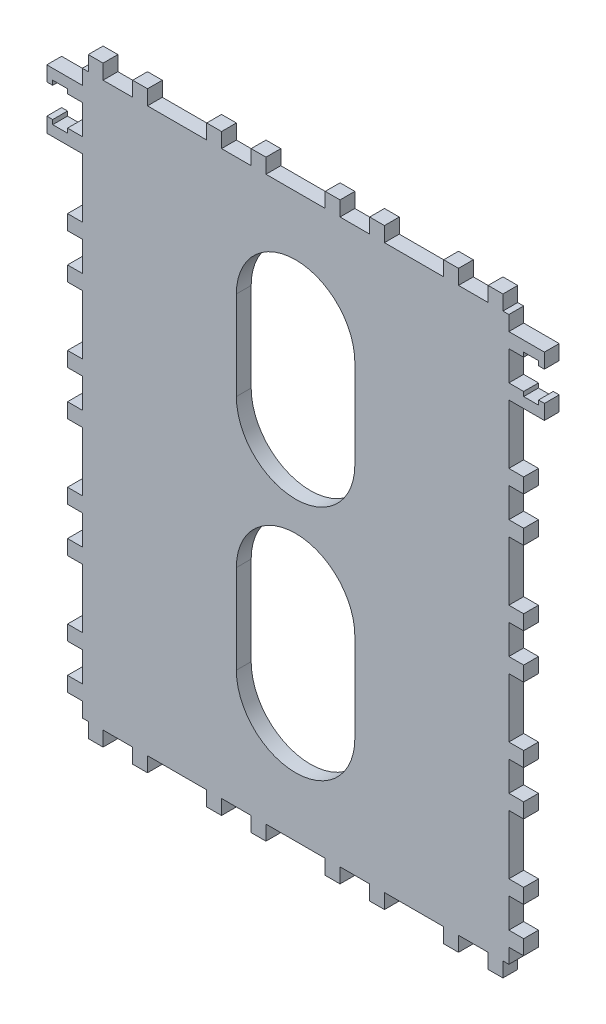
SolidWorks part; units mm, degrees
ref_plane "Plan de face" through (0, 0, 0) normal (0, 0, 1) x (1, 0, 0)
ref_plane "Plan de dessus" through (0, 0, 0) normal (0, 1, 0) x (1, 0, 0)
ref_plane "Plan de droite" through (0, 0, 0) normal (1, 0, 0) x (0, 0, -1)
sketch "Esquisse1" plane through (0, 0, 0) normal (0, 0, 1) x (1, 0, 0)
  line L0 (0, 0) -> (0, 95) construction
  line L1 (-27.1299, 95) -> (22.3044, 95) construction
  line L2 (0, 40) -> (0, 70) construction
  line L3 (-72, 190) -> (-72, 0) construction
  line L4 (-72, 0) -> (-70, 0)
  line L5 (70, 0) -> (72, 0)
  line L6 (-50, 190) -> (-30, 190)
  line L7 (72, 0) -> (72, 190) construction
  line L8 (-20, 40) -> (-20, 70)
  line L9 (50, 190) -> (30, 190)
  line L10 (10, 190) -> (-10, 190)
  line L11 (10, 0) -> (-10, 0)
  line L12 (50, 0) -> (30, 0)
  line L13 (-50, 0) -> (-30, 0)
  line L14 (-72, 5) -> (-72, 0)
  line L15 (-72, 25) -> (-72, 45)
  line L16 (-72, 65) -> (-72, 85)
  line L17 (-72, 105) -> (-72, 125)
  line L18 (-72, 145) -> (-72, 165)
  line L19 (-72, 185) -> (-72, 190)
  line L20 (72, 190) -> (72, 0) construction
  line L21 (72, 185) -> (72, 190)
  line L22 (72, 145) -> (72, 165)
  line L23 (72, 105) -> (72, 125)
  line L24 (72, 65) -> (72, 85)
  line L25 (72, 25) -> (72, 45)
  line L26 (72, 5) -> (72, 0)
  line L27 (70, 190) -> (72, 190)
  line L28 (-72, 190) -> (-70, 190)
  line L29 (20, 40) -> (20, 70)
  line L30 (0, 120) -> (0, 150) construction
  line L31 (-20, 120) -> (-20, 150)
  line L32 (20, 120) -> (20, 150)
  arc A0 (-20, 40) -> (20, 40) centre (0, 40) ccw
  arc A1 (20, 70) -> (-20, 70) centre (0, 70) ccw
  arc A2 (-20, 120) -> (20, 120) centre (0, 120) ccw
  arc A3 (20, 150) -> (-20, 150) centre (0, 150) ccw
  point P15 (0, 55)
  point P46 (0, 135)
  point P59 (0, 20)
  point P60 (0, 0)
  point P61 (0, 0)
  line B0 (-60, 0) -> (-60, 11.1075) construction
  line B1 (-60, 0) -> (-65, 0)
  line B2 (-65, -5) -> (-70, -5)
  line B3 (-70, -5) -> (-70, 0)
  line B4 (-65, -5) -> (-65, 0)
  line B5 (-60, 0) -> (-55, 0)
  line B6 (-55, 0) -> (-55, -5)
  line B7 (-55, -5) -> (-50, -5)
  line B8 (-50, -5) -> (-50, 0)
  line B9 (-20, 0) -> (-20, 11.1075) construction
  line B10 (-20, 0) -> (-25, 0)
  line B11 (-25, -5) -> (-30, -5)
  line B12 (-30, -5) -> (-30, 0)
  line B13 (-25, -5) -> (-25, 0)
  line B14 (-20, 0) -> (-15, 0)
  line B15 (-15, 0) -> (-15, -5)
  line B16 (-15, -5) -> (-10, -5)
  line B17 (-10, -5) -> (-10, 0)
  line B18 (60, 0) -> (60, 11.1075) construction
  line B19 (60, 0) -> (65, 0)
  line B20 (65, -5) -> (70, -5)
  line B21 (70, -5) -> (70, 0)
  line B22 (65, -5) -> (65, 0)
  line B23 (60, 0) -> (55, 0)
  line B24 (55, 0) -> (55, -5)
  line B25 (55, -5) -> (50, -5)
  line B26 (50, -5) -> (50, 0)
  line B27 (-72, 135) -> (-60.8925, 135) construction
  line B28 (-72, 135) -> (-72, 130)
  line B29 (-77, 130) -> (-77, 125)
  line B30 (-77, 125) -> (-72, 125)
  line B31 (-77, 130) -> (-72, 130)
  line B32 (-72, 135) -> (-72, 140)
  line B33 (-72, 140) -> (-77, 140)
  line B34 (-77, 140) -> (-77, 145)
  line B35 (-77, 145) -> (-72, 145)
  line B36 (-72, 95) -> (-60.8925, 95) construction
  line B37 (-72, 95) -> (-72, 90)
  line B38 (-77, 90) -> (-77, 85)
  line B39 (-77, 85) -> (-72, 85)
  line B40 (-77, 90) -> (-72, 90)
  line B41 (-72, 95) -> (-72, 100)
  line B42 (-72, 100) -> (-77, 100)
  line B43 (-77, 100) -> (-77, 105)
  line B44 (-77, 105) -> (-72, 105)
  line B45 (-72, 55) -> (-60.8925, 55) construction
  line B46 (-72, 55) -> (-72, 50)
  line B47 (-77, 50) -> (-77, 45)
  line B48 (-77, 45) -> (-72, 45)
  line B49 (-77, 50) -> (-72, 50)
  line B50 (-72, 55) -> (-72, 60)
  line B51 (-72, 60) -> (-77, 60)
  line B52 (-77, 60) -> (-77, 65)
  line B53 (-77, 65) -> (-72, 65)
  line B54 (-72, 15) -> (-60.8925, 15) construction
  line B55 (-72, 15) -> (-72, 10)
  line B56 (-77, 10) -> (-77, 5)
  line B57 (-77, 5) -> (-72, 5)
  line B58 (-77, 10) -> (-72, 10)
  line B59 (-72, 15) -> (-72, 20)
  line B60 (-72, 20) -> (-77, 20)
  line B61 (-77, 20) -> (-77, 25)
  line B62 (-77, 25) -> (-72, 25)
  line B63 (72, 55) -> (60.8925, 55) construction
  line B64 (72, 55) -> (72, 50)
  line B65 (77, 50) -> (77, 45)
  line B66 (77, 45) -> (72, 45)
  line B67 (77, 50) -> (72, 50)
  line B68 (72, 55) -> (72, 60)
  line B69 (72, 60) -> (77, 60)
  line B70 (77, 60) -> (77, 65)
  line B71 (77, 65) -> (72, 65)
  line B72 (72, 15) -> (60.8925, 15) construction
  line B73 (72, 15) -> (72, 10)
  line B74 (77, 10) -> (77, 5)
  line B75 (77, 5) -> (72, 5)
  line B76 (77, 10) -> (72, 10)
  line B77 (72, 15) -> (72, 20)
  line B78 (72, 20) -> (77, 20)
  line B79 (77, 20) -> (77, 25)
  line B80 (77, 25) -> (72, 25)
  line B81 (72, 95) -> (60.8925, 95) construction
  line B82 (72, 95) -> (72, 90)
  line B83 (77, 90) -> (77, 85)
  line B84 (77, 85) -> (72, 85)
  line B85 (77, 90) -> (72, 90)
  line B86 (72, 95) -> (72, 100)
  line B87 (72, 100) -> (77, 100)
  line B88 (77, 100) -> (77, 105)
  line B89 (77, 105) -> (72, 105)
  line B90 (72, 135) -> (60.8925, 135) construction
  line B91 (72, 135) -> (72, 130)
  line B92 (77, 130) -> (77, 125)
  line B93 (77, 125) -> (72, 125)
  line B94 (77, 130) -> (72, 130)
  line B95 (72, 135) -> (72, 140)
  line B96 (72, 140) -> (77, 140)
  line B97 (77, 140) -> (77, 145)
  line B98 (77, 145) -> (72, 145)
  line B99 (72, 175) -> (60.135, 175) construction
  line B100 (72, 175) -> (72, 170)
  line B101 (77, 170) -> (77, 165) construction
  line B102 (77, 165) -> (72, 165)
  line B103 (77, 170) -> (72, 170)
  line B104 (72, 175) -> (72, 180)
  line B105 (72, 180) -> (77, 180)
  line B106 (77, 180) -> (77, 185) construction
  line B107 (77, 185) -> (72, 185)
  line B108 (77, 165) -> (84, 165)
  line B109 (84, 165) -> (84, 170)
  line B110 (84, 170) -> (82, 170)
  line B111 (82, 170) -> (82, 168.5)
  line B112 (82, 168.5) -> (77, 168.5)
  line B113 (77, 168.5) -> (77, 170)
  line B114 (82, 180) -> (82, 181.5)
  line B115 (84, 185) -> (84, 180)
  line B116 (84, 180) -> (82, 180)
  line B117 (82, 181.5) -> (77, 181.5)
  line B118 (77, 185) -> (84, 185)
  line B119 (77, 185) -> (72, 185)
  line B120 (77, 180) -> (77, 181.5)
  line B121 (-72, 175) -> (-60.135, 175) construction
  line B122 (-72, 175) -> (-72, 170)
  line B123 (-77, 170) -> (-77, 165) construction
  line B124 (-77, 165) -> (-72, 165)
  line B125 (-77, 170) -> (-72, 170)
  line B126 (-72, 175) -> (-72, 180)
  line B127 (-72, 180) -> (-77, 180)
  line B128 (-77, 180) -> (-77, 185) construction
  line B129 (-77, 185) -> (-72, 185)
  line B130 (-77, 165) -> (-84, 165)
  line B131 (-84, 165) -> (-84, 170)
  line B132 (-84, 170) -> (-82, 170)
  line B133 (-82, 170) -> (-82, 168.5)
  line B134 (-82, 168.5) -> (-77, 168.5)
  line B135 (-77, 168.5) -> (-77, 170)
  line B136 (-82, 180) -> (-82, 181.5)
  line B137 (-84, 185) -> (-84, 180)
  line B138 (-84, 180) -> (-82, 180)
  line B139 (-82, 181.5) -> (-77, 181.5)
  line B140 (-77, 185) -> (-84, 185)
  line B141 (-77, 185) -> (-72, 185)
  line B142 (-77, 180) -> (-77, 181.5)
  line B143 (20, 0) -> (20, 11.1075) construction
  line B144 (20, 0) -> (25, 0)
  line B145 (25, -5) -> (30, -5)
  line B146 (30, -5) -> (30, 0)
  line B147 (25, -5) -> (25, 0)
  line B148 (20, 0) -> (15, 0)
  line B149 (15, 0) -> (15, -5)
  line B150 (15, -5) -> (10, -5)
  line B151 (10, -5) -> (10, 0)
  line B152 (20, 190) -> (20, 178.8925) construction
  line B153 (20, 190) -> (25, 190)
  line B154 (25, 195) -> (30, 195)
  line B155 (30, 195) -> (30, 190)
  line B156 (25, 195) -> (25, 190)
  line B157 (20, 190) -> (15, 190)
  line B158 (15, 190) -> (15, 195)
  line B159 (15, 195) -> (10, 195)
  line B160 (10, 195) -> (10, 190)
  line B161 (-60, 190) -> (-60, 178.8925) construction
  line B162 (-60, 190) -> (-65, 190)
  line B163 (-65, 195) -> (-70, 195)
  line B164 (-70, 195) -> (-70, 190)
  line B165 (-65, 195) -> (-65, 190)
  line B166 (-60, 190) -> (-55, 190)
  line B167 (-55, 190) -> (-55, 195)
  line B168 (-55, 195) -> (-50, 195)
  line B169 (-50, 195) -> (-50, 190)
  line B170 (-20, 190) -> (-20, 178.8925) construction
  line B171 (-20, 190) -> (-25, 190)
  line B172 (-25, 195) -> (-30, 195)
  line B173 (-30, 195) -> (-30, 190)
  line B174 (-25, 195) -> (-25, 190)
  line B175 (-20, 190) -> (-15, 190)
  line B176 (-15, 190) -> (-15, 195)
  line B177 (-15, 195) -> (-10, 195)
  line B178 (-10, 195) -> (-10, 190)
  line B179 (60, 190) -> (60, 178.8925) construction
  line B180 (60, 190) -> (65, 190)
  line B181 (65, 195) -> (70, 195)
  line B182 (70, 195) -> (70, 190)
  line B183 (65, 195) -> (65, 190)
  line B184 (60, 190) -> (55, 190)
  line B185 (55, 190) -> (55, 195)
  line B186 (55, 195) -> (50, 195)
  line B187 (50, 195) -> (50, 190)
sketch_block_instance "Insert M3 plots ep 5mm-9"
sketch_block "Insert M3 plots ep 5mm" parameters "D1"=10, "D2"=5, "D3"=5
sketch_block_instance "Insert M3 plots ep 5mm-11"
sketch_block_instance "Insert M3 plots ep 5mm-12"
sketch_block_instance "Insert M3 plots ep 5mm-14"
sketch_block_instance "Insert M3 plots ep 5mm-15"
sketch_block_instance "Insert M3 plots ep 5mm-16"
sketch_block_instance "Insert M3 plots ep 5mm-17"
sketch_block_instance "Insert M3 plots ep 5mm-19"
sketch_block_instance "Insert M3 plots ep 5mm-20"
sketch_block_instance "Insert M3 plots ep 5mm-21"
sketch_block_instance "Insert M3 plots ep 5mm-22"
sketch_block_instance "Insert plots ep 5mm avec ergots-1"
sketch_block "Insert plots ep 5mm avec ergots" parameters "D1"=10, "D2"=5, "D3"=5, "D4"=5, "D5"=2, "D6"=1.5, "D7"=2, "D8"=2, "D9"=2.0716, "D10"=2
sketch_block_instance "Insert plots ep 5mm avec ergots-3"
sketch_block_instance "Insert M3 plots ep 5mm-24"
sketch_block_instance "Insert M3 plots ep 5mm-25"
sketch_block_instance "Insert M3 plots ep 5mm-26"
sketch_block_instance "Insert M3 plots ep 5mm-27"
sketch_block_instance "Insert M3 plots ep 5mm-28" parameters "D15"=20, "D1"=0, "D2"=11.4238, "D3"=90.6659, "D4"=90.4393, "D5"=190, "D6"=58.1047, "D7"=31.0035, "D8"=12.9902, "D9"=20, "D10"=32.6137, "D11"=20, "D12"=62, "D13"=30, "D14"=110
extrude "Boss.-Extru.1" add sketch "Esquisse1" along normal blind 5
